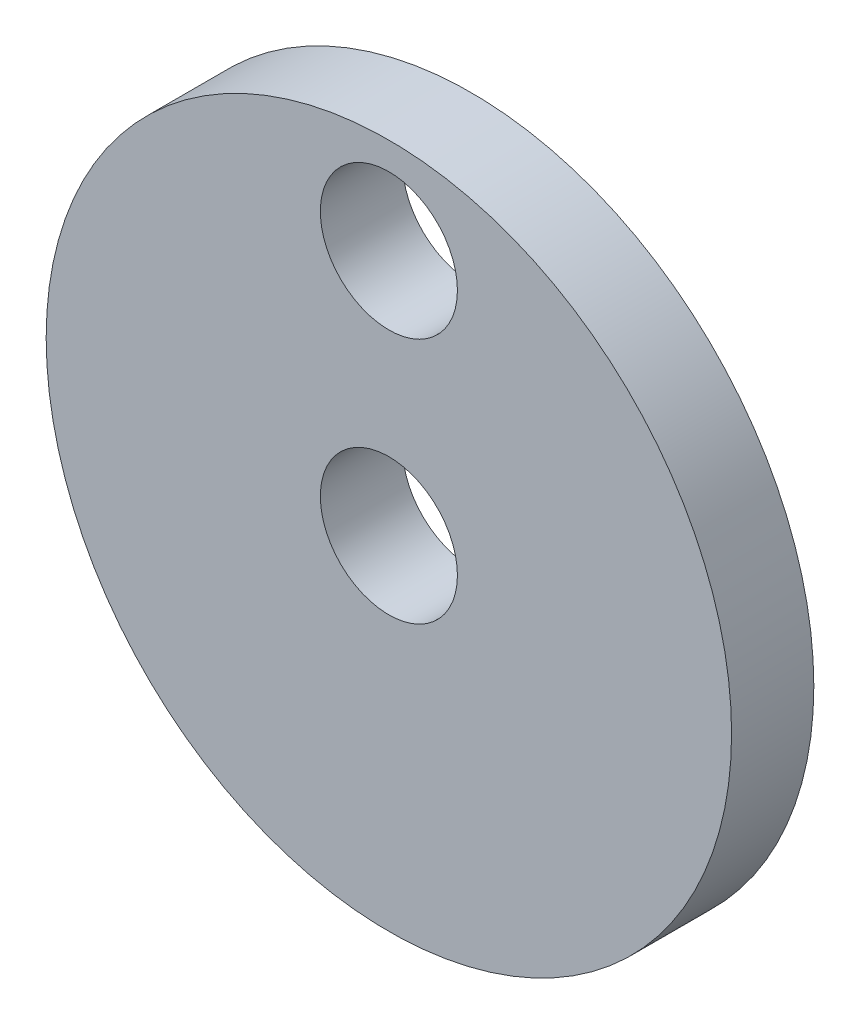
SolidWorks part; units mm, degrees
ref_plane "前基準面" through (0, 0, 0) normal (0, 0, 1) x (1, 0, 0)
ref_plane "上基準面" through (0, 0, 0) normal (0, 1, 0) x (1, 0, 0)
ref_plane "右基準面" through (0, 0, 0) normal (1, 0, 0) x (0, 0, -1)
sketch "草圖1" plane through (0, 0, 0) normal (0, 0, 1) x (1, 0, 0)
  circle A0 centre (0, 0) radius 9 construction
  circle A1 centre (0, 0) radius 12.5
  circle A2 centre (0, 0) radius 2.5
  circle A3 centre (0, 9) radius 2.5
  dimension "D1" = 18
  dimension "D2" = 25
  dimension "D3" = 5
  dimension "D4" = 5
extrude "填料-伸長1" add sketch "草圖1" along normal blind 3
